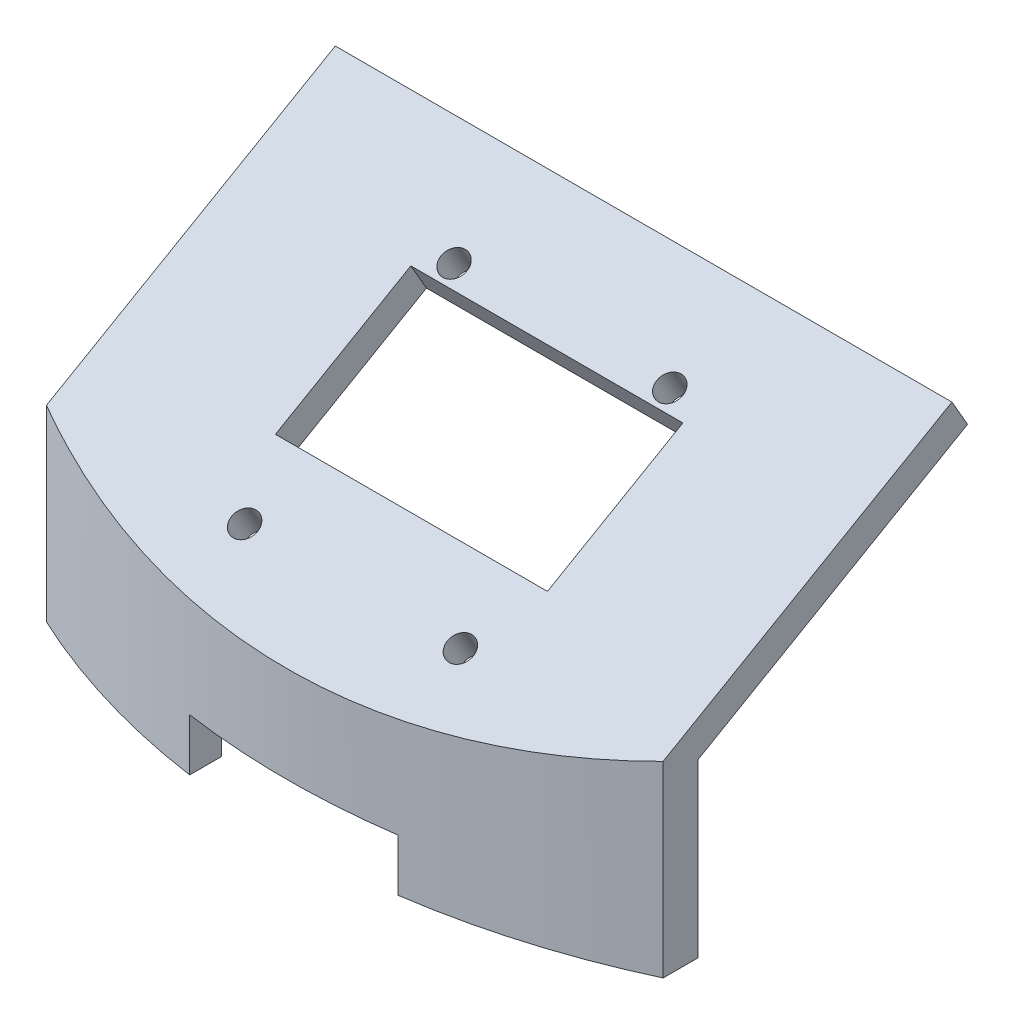
SolidWorks part; units mm, degrees
ref_plane "Front Plane" through (0, 0, 0) normal (0, 0, 1) x (1, 0, 0)
ref_plane "Top Plane" through (0, 0, 0) normal (0, 1, 0) x (1, 0, 0)
ref_plane "Right Plane" through (0, 0, 0) normal (1, 0, 0) x (0, 0, -1)
sketch "Sketch1" plane through (0, 0, 0) normal (0, 1, 0) x (1, 0, 0)
  line L0 (0, 0) -> (0, 50000) construction
  line L1 (0, 0) -> (-29.5833, -63.4415) construction
  line L2 (29.5833, -63.4415) -> (0, 0) construction
  line L5 (-29.5833, -63.4415) -> (-29.5833, -60.1151)
  line L6 (29.5833, -63.4415) -> (29.5833, -60.1151)
  arc A0 (-29.5833, -63.4415) -> (29.5833, -63.4415) centre (0, 0) ccw
  arc A1 (-29.5833, -60.1151) -> (29.5833, -60.1151) centre (0, 0) ccw
  dimension "D3" = 70
  dimension "D5" = 67
  dimension "D1" = 25
  dimension "D2" = 25
extrude "Boss-Extrude1" add sketch "Sketch1" along normal blind 18
sketch "Sketch2" plane through (0, 0, 0) normal (1, 0, 0) x (0, 0, -1)
  line L0 (-94.6185, 0) -> (-70, 14.2135)
  line L1 (0, 0) -> (-50000, 0) construction
  line L2 (-70, 18) -> (-70, 0) construction
  line L3 (-70, 14.2135) -> (-63.4415, 18) construction
  point P4 (0, 0)
  dimension "D1" = 30
ref_plane "Plane1" through (0, 40.971, 23.6546) normal (0, -0.866, -0.5) x (-1, 0, 0)
sketch "Sketch3" plane through (0, 40.971, 23.6546) normal (0, -0.866, -0.5) x (-1, 0, 0)
  line L0 (29.5833, -43.0612) -> (29.5833, -52.0612) construction
  line L1 (29.5833, -45.942) -> (-29.5833, -45.942) construction
  line L2 (29.5833, -45.942) -> (29.5833, -13.942)
  line L3 (29.5833, -13.942) -> (-29.5833, -13.942)
  line L4 (-29.5833, -45.942) -> (-29.5833, -13.942)
  line L6 (-29.5833, -45.942) -> (-29.5833, -53.515)
  line L7 (-29.5833, -53.515) -> (29.5833, -53.515)
  line L8 (29.5833, -45.942) -> (29.5833, -53.515)
  dimension "D1" = 32
extrude "Boss-Extrude2" add sketch "Sketch3" along normal blind 3
sketch "Sketch7" plane through (0, 0, 0) normal (1, 0, 0) x (0, 0, -1)
  line L1 (-70, 14.2135) -> (-63.4415, 18)
  line L2 (-63.4415, 18) -> (-70, 18)
  line L6 (0, 0) -> (0, 24.725) construction
  line L7 (-70, 18) -> (-70, 14.2135) construction
  line L8 (-70, 14.2135) -> (-70, 18)
extrude "Cut-Extrude3" cut sketch "Sketch7" against normal through all and the other way through all
sketch "Sketch8" plane through (0, 0, 0) normal (0, -1, 0) x (1, 0, 0)
  line L0 (29.5833, 63.4415) -> (29.5833, 60.1151) construction
  line L1 (-29.5833, 63.4415) -> (-29.5833, 71.5498)
  line L2 (-29.5833, 71.5498) -> (29.5833, 71.5498)
  line L3 (29.5833, 71.5498) -> (29.5833, 63.4415)
  arc A0 (-29.5833, 63.4415) -> (29.5833, 63.4415) centre (0, 0) cw
  point P7 (0, 0)
extrude "Cut-Extrude4" cut sketch "Sketch8" against normal through all
sketch "Sketch5" plane through (0, 40.971, 23.6546) normal (0, 0.866, 0.5) x (1, 0, 0)
  line L0 (0, -48.242) -> (0, -20.942) construction
  line L5 (-29.5833, -13.942) -> (29.5833, -13.942) construction
  line L7 (29.5408, -34.592) -> (-29.5408, -34.592) construction
  line L8 (0, -20.942) -> (0, -13.942) construction
  line L9 (-10.35, -22.992) -> (10.35, -22.992) construction
  line L10 (-10.35, -22.992) -> (-10.35, -46.192) construction
  line L11 (-13.05, -39.662) -> (13.05, -39.662)
  line L12 (-13.05, -39.662) -> (-13.05, -24.662)
  line L13 (-13.05, -24.662) -> (13.05, -24.662)
  line L14 (13.05, -39.662) -> (13.05, -24.662)
  line L15 (-13.05, -39.662) -> (13.05, -24.662) construction
  line L16 (-13.05, -24.662) -> (13.05, -39.662) construction
  line L20 (-13.65, -48.242) -> (13.65, -48.242) construction
  line L21 (-13.65, -48.242) -> (-13.65, -20.942) construction
  line L22 (-13.65, -20.942) -> (13.65, -20.942) construction
  line L23 (13.65, -48.242) -> (13.65, -20.942) construction
  line L24 (-13.65, -48.242) -> (13.65, -20.942) construction
  line L25 (-13.65, -20.942) -> (13.65, -48.242) construction
  line L27 (0, -48.242) -> (0, -49.242) construction
  circle A0 centre (-10.35, -22.992) radius 1.25
  circle A1 centre (10.35, -22.992) radius 1.25
  circle A2 centre (10.35, -46.192) radius 1.25
  circle A3 centre (-10.35, -46.192) radius 1.25
  point P0 (0, -32.162)
  point P13 (0, -25.112)
  point P24 (0, -34.592)
  point P32 (0, -41.1669)
  point P33 (0, 0)
  dimension "D6" = 2.5
  dimension "D7" = 3.3
  dimension "D8" = 2.05
  dimension "D13" = 1
  dimension "D1" = 15
  dimension "D2" = 26.1
  dimension "D3" = 11.22
  dimension "D4" = 27.3
  dimension "D5" = 27.3
  dimension "D11" = 20.7
  dimension "D12" = 23.2
  dimension "D14" = 7
  dimension "D9" = 2
  dimension "D10" = 2
extrude "Cut-Extrude1" cut sketch "Sketch5" against normal blind 7
sketch "Sketch6" plane through (0, 0, 0) normal (0, 0, 1) x (1, 0, 0)
  line L1 (-10, -5) -> (10, -5)
  line L2 (-10, -5) -> (-10, 5)
  line L3 (-10, 5) -> (10, 5)
  line L4 (10, -5) -> (10, 5)
  line L5 (-10, -5) -> (10, 5) construction
  line L6 (-10, 5) -> (10, -5) construction
  point P0 (0, 0)
  dimension "D1" = 5
  dimension "D2" = 20
extrude "Cut-Extrude2" cut sketch "Sketch6" along normal through all
